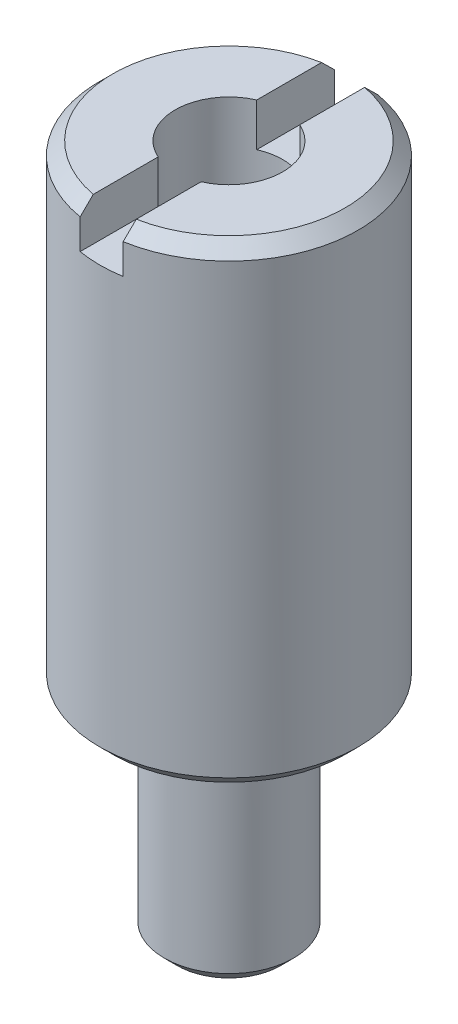
SolidWorks part; units mm, degrees
material "A2017"
ref_plane "正面" through (0, 0, 0) normal (0, 0, 1) x (1, 0, 0)
ref_plane "平面" through (0, 0, 0) normal (0, 1, 0) x (1, 0, 0)
ref_plane "右側面" through (0, 0, 0) normal (1, 0, 0) x (0, 0, -1)
sketch "ｽｹｯﾁ1" plane through (0, 0, 0) normal (0, 0, 1) x (1, 0, 0)
  line L0 (0, 16.0048) -> (0, -5) construction
  line L1 (0, -5) -> (-1.5, -5)
  line L2 (-1.5, -5) -> (-1.5, 0)
  line L3 (-1.5, 0) -> (-3, 0)
  line L4 (-3, 0) -> (-3, 11)
  line L5 (-3, 11) -> (0, 11)
  line L6 (0, -5) -> (0, 11)
  dimension "D1" = 3
  dimension "D2" = 5
  dimension "D3" = 11
  dimension "D4" = 6
revolve "回転1" add sketch "ｽｹｯﾁ1" angle 360 about L0
chamfer "面取り1" distance 0.3 angle 45 3 edges at (-3, 11, 0) (-3, 0, 0) (-1.5, -5, 0)
sketch "ｽｹｯﾁ2" plane through (0, 11, 0) normal (0, 1, 0) x (1, 0, 0)
  line L1 (0.5, -2.958) -> (-0.5, -2.958) construction
  line L2 (0.5, -2.958) -> (0.5, 2.958)
  line L3 (0.5, 2.958) -> (-0.5, 2.958) construction
  line L4 (-0.5, -2.958) -> (-0.5, 2.958)
  line L5 (0.5, -2.958) -> (-0.5, 2.958) construction
  line L6 (0.5, 2.958) -> (-0.5, -2.958) construction
  circle A0 centre (0, 0) radius 3 construction
  arc A1 (0.5, 2.958) -> (-0.5, 2.958) centre (0, 0) ccw
  arc A2 (-0.5, -2.958) -> (0.5, -2.958) centre (0, 0) ccw
  point P0 (0, 0)
  dimension "D1" = 1
extrude "ｶｯﾄ - 押し出し2" cut sketch "ｽｹｯﾁ2" against normal blind 1
hole_wizard "M3 ねじ穴1" positions "ｽｹｯﾁ3" profile "ｽｹｯﾁ4" tap size "M3" standard "JIS"
sketch "ｽｹｯﾁ3" plane through (0, 11, 0) normal (0, 1, 0) x (1, 0, 0)
  point P0 (0, 0)
sketch "ｽｹｯﾁ4" plane through (0, 11, 0) normal (1, 0, 0) x (0, 0, 1)
  line L0 (0, 0) -> (0, 9.2511)
  line L1 (0, 9.2511) -> (1.25, 8.5)
  line L2 (1.25, 8.5) -> (1.25, 0)
  line L5 (1.25, 0) -> (0, 0)
  line L10 (0, 9.2511) -> (-1.25, 8.5) construction
  line L11 (0, -6.35) -> (0, 107.95) construction
  dimension "ねじ下穴ﾄﾞﾘﾙ直径" = 2.5
  dimension "ねじ下穴ﾄﾞﾘﾙの深さ" = 8.5
  dimension "ﾄﾞﾘﾙ角度" = 118
cosmetic thread "穴のねじ山1" parameters "D1"=6, "D2"=3
